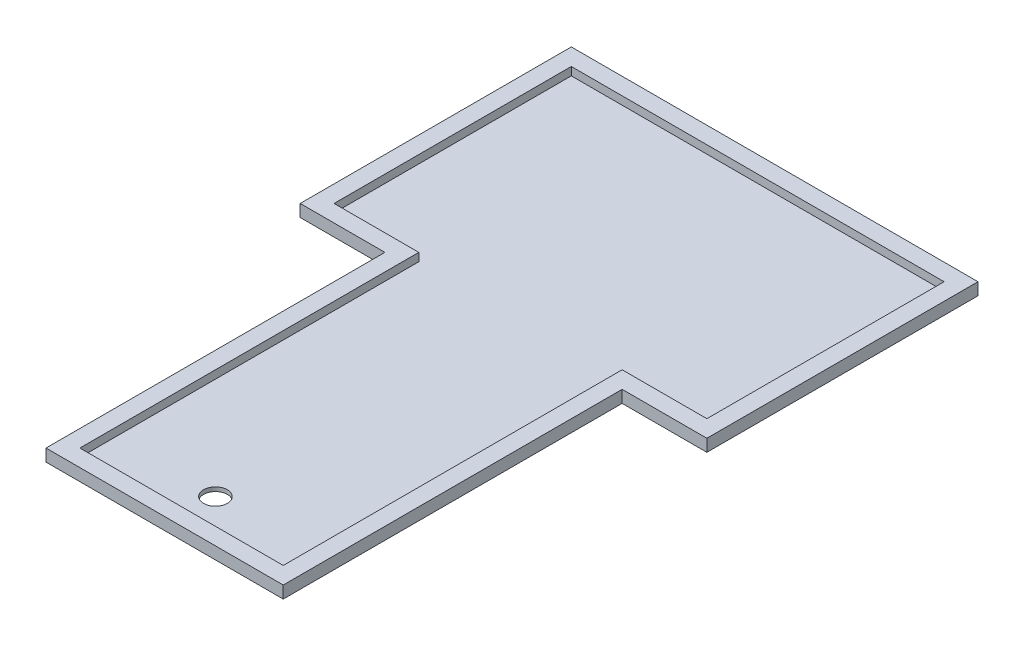
SolidWorks part; units mm, degrees
ref_plane "Front Plane" through (0, 0, 0) normal (0, 0, 1) x (1, 0, 0)
ref_plane "Top Plane" through (0, 0, 0) normal (0, 1, 0) x (1, 0, 0)
ref_plane "Right Plane" through (0, 0, 0) normal (1, 0, 0) x (0, 0, -1)
sketch "Sketch1" plane through (0, 0, 0) normal (0, 1, 0) x (1, 0, 0)
  line L0 (0, 0) -> (0, -173.0724) construction
  line L1 (-60, -40) -> (-35, -40)
  line L2 (-60, -40) -> (-60, 40)
  line L3 (-60, 40) -> (60, 40)
  line L4 (60, -40) -> (60, 40)
  line L5 (-60, -40) -> (60, 40) construction
  line L6 (-60, 40) -> (60, -40) construction
  line L7 (35, -40) -> (60, -40)
  line L8 (-35, -140) -> (35, -140)
  line L9 (-35, -140) -> (-35, -40)
  line L10 (-113.7115, 0) -> (113.7115, 0) construction
  line L11 (35, -140) -> (35, -40)
  line L12 (-35, -140) -> (35, -40) construction
  line L13 (-35, -40) -> (35, -140) construction
  circle A0 centre (0, -125) radius 3.5
  point P0 (0, 0)
  point P8 (0, -90)
  point P18 (0, 0)
  dimension "D5" = 7
  dimension "D1" = 120
  dimension "D2" = 80
  dimension "D3" = 100
  dimension "D4" = 70
  dimension "D6" = 15
extrude "Boss-Extrude1" add sketch "Sketch1" along normal blind 1.2
sketch "Sketch2" plane through (0, 1.2, 0) normal (0, 1, 0) x (1, 0, 0)
  line L0 (99.159, 0) -> (-99.159, 0) construction
  line L1 (-60, -40) -> (-35, -40)
  line L2 (-60, -40) -> (-60, 0)
  line L3 (-60, 40) -> (60, 40)
  line L4 (60, -40) -> (60, 0)
  line L5 (-60, -40) -> (60, 40) construction
  line L6 (-60, 40) -> (60, -40) construction
  line L7 (-55, -35) -> (-30, -35)
  line L8 (-55, -35) -> (-55, 0)
  line L9 (-55, 35) -> (55, 35)
  line L10 (55, -35) -> (55, 0)
  line L11 (-55, -35) -> (55, 35) construction
  line L12 (-55, 35) -> (55, -35) construction
  line L17 (60, 0) -> (60, 40)
  line L18 (55, 0) -> (55, 35)
  line L19 (-55, 0) -> (-55, 35)
  line L20 (-60, 0) -> (-60, 40)
  line L21 (0, 0) -> (0, -161.941) construction
  line L22 (-35, -40) -> (-35, -140)
  line L23 (-35, -140) -> (35, -140)
  line L24 (35, -140) -> (35, -40)
  line L25 (35, -140) -> (35, -40) construction
  line L26 (30, -35) -> (30, -135)
  line L27 (30, -135) -> (-30, -135)
  line L28 (-30, -135) -> (-30, -35)
  line L29 (30, -35) -> (55, -35)
  line L30 (35, -40) -> (60, -40)
  point P0 (0, 0)
  point P7 (0, 0)
  point P15 (0, 0)
  dimension "D1" = 110
  dimension "D2" = 70
  dimension "D7" = 5
  dimension "D8" = 5
  dimension "D9" = 5
extrude "Boss-Extrude2" add sketch "Sketch2" along normal blind 2.4
